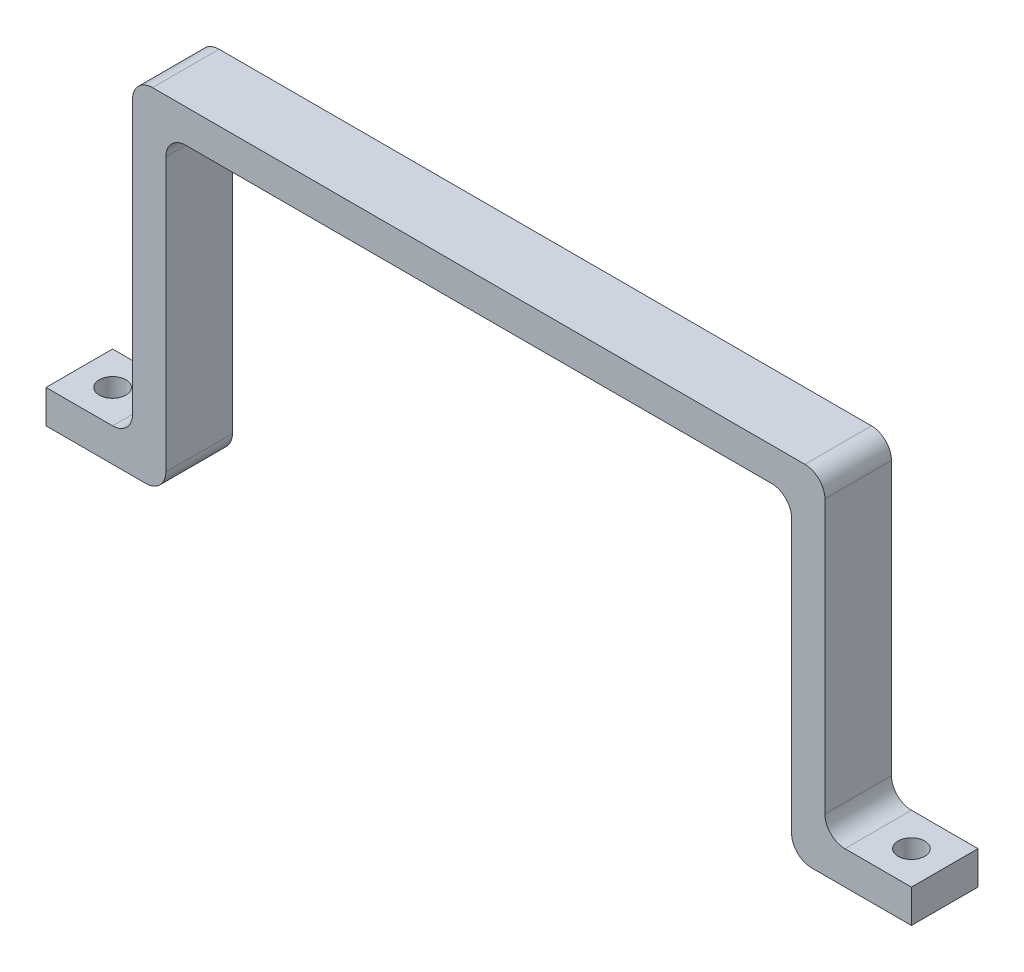
SolidWorks part; units mm, degrees
ref_plane "Front Plane" through (0, 0, 0) normal (0, 0, 1) x (1, 0, 0)
ref_plane "Top Plane" through (0, 0, 0) normal (0, 1, 0) x (1, 0, 0)
ref_plane "Right Plane" through (0, 0, 0) normal (1, 0, 0) x (0, 0, -1)
sketch "Sketch1" plane through (0, 0, 0) normal (0, 0, 1) x (1, 0, 0)
  line L0 (52, -15.5) -> (52, 25.5)
  line L2 (47, -20.5) -> (47, 20.5)
  line L3 (44, 23.5) -> (-44, 23.5)
  line L4 (-47, -20.5) -> (-47, 20.5)
  line L5 (47, -23.5) -> (-47, 23.5) construction
  line L6 (47, 23.5) -> (-47, -23.5) construction
  line L7 (49, 28.5) -> (-49, 28.5)
  line L8 (-52, -15.5) -> (-52, 25.5)
  line L10 (-55, -18.5) -> (-65, -18.5)
  line L11 (-65, -18.5) -> (-65, -23.5)
  line L12 (-65, -23.5) -> (-52, -23.5)
  line L13 (-50, -23.5) -> (-52, -23.5)
  line L14 (50, -23.5) -> (52, -23.5)
  line L16 (-52, -23.5) -> (-52, 28.5) construction
  line L17 (65, -23.5) -> (52, -23.5)
  line L18 (65, -18.5) -> (65, -23.5)
  line L19 (55, -18.5) -> (65, -18.5)
  line L20 (52, -23.5) -> (52, 28.5) construction
  line L21 (-47, -23.5) -> (-47, 23.5) construction
  line L22 (47, -23.5) -> (47, 23.5) construction
  line L23 (52, 28.5) -> (-52, 28.5) construction
  line L24 (47, 23.5) -> (-47, 23.5) construction
  arc A0 (-50, -23.5) -> (-47, -20.5) centre (-50, -20.5) ccw
  arc A1 (-52, -15.5) -> (-55, -18.5) centre (-55, -15.5) cw
  arc A2 (50, -23.5) -> (47, -20.5) centre (50, -20.5) cw
  arc A3 (55, -18.5) -> (52, -15.5) centre (55, -15.5) cw
  arc A4 (52, 25.5) -> (49, 28.5) centre (49, 25.5) ccw
  arc A5 (47, 20.5) -> (44, 23.5) centre (44, 20.5) ccw
  arc A6 (-49, 28.5) -> (-52, 25.5) centre (-49, 25.5) ccw
  arc A7 (-44, 23.5) -> (-47, 20.5) centre (-44, 20.5) ccw
  point P0 (0, 0)
  dimension "D2" = 3
  dimension "D1" = 5
extrude "Boss-Extrude1" add sketch "Sketch1" along normal blind 10
sketch "Sketch2" plane through (0, -18.5, 0) normal (0, 1, 0) x (1, 0, 0)
  circle A0 centre (-60, -5) radius 2
  circle A1 centre (60, -5) radius 2
extrude "Cut-Extrude1" cut sketch "Sketch2" against normal through all
